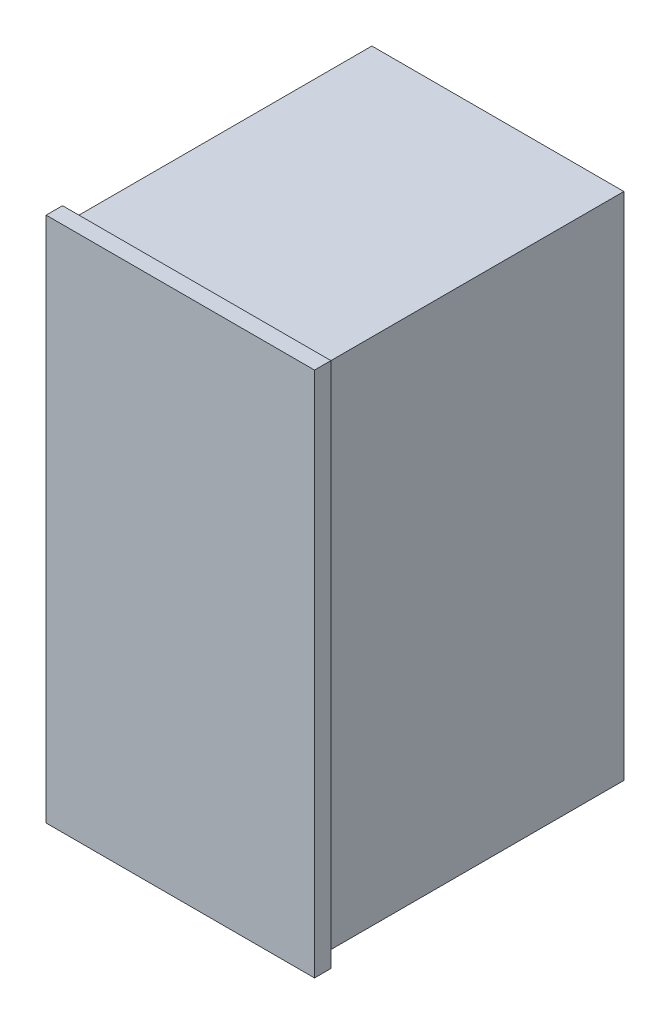
SolidWorks part; units mm, degrees
ref_plane "Front Plane" through (0, 0, 0) normal (0, 0, 1) x (1, 0, 0)
ref_plane "Top Plane" through (0, 0, 0) normal (0, 1, 0) x (1, 0, 0)
ref_plane "Right Plane" through (0, 0, 0) normal (1, 0, 0) x (0, 0, -1)
sketch "Sketch3" plane through (0, 0, 0) normal (0, 1, 0) x (1, 0, 0)
  line L1 (0, 0) -> (123, 0)
  line L2 (0, 0) -> (0, 147)
  line L3 (0, 147) -> (123, 147)
  line L4 (123, 0) -> (123, 147)
  dimension "D1" = 147
  dimension "D2" = 123
extrude "Boss-Extrude1" add sketch "Sketch3" along normal blind 249
sketch "Sketch4" plane through (0, 0, 0) normal (0, 1, 0) x (1, 0, 0)
  line L0 (-4, 0) -> (127, 0)
  line L5 (127, 0) -> (127, -8)
  line L6 (127, -8) -> (-4, -8)
  line L7 (-4, -8) -> (-4, 0)
  line L8 (0, 147) -> (0, 0) construction
  line L9 (123, 0) -> (123, 147) construction
  dimension "D1" = 8
  dimension "D2" = 4
  dimension "D3" = 4
extrude "Boss-Extrude2" add sketch "Sketch4" along normal blind 253 and the other way blind 4
